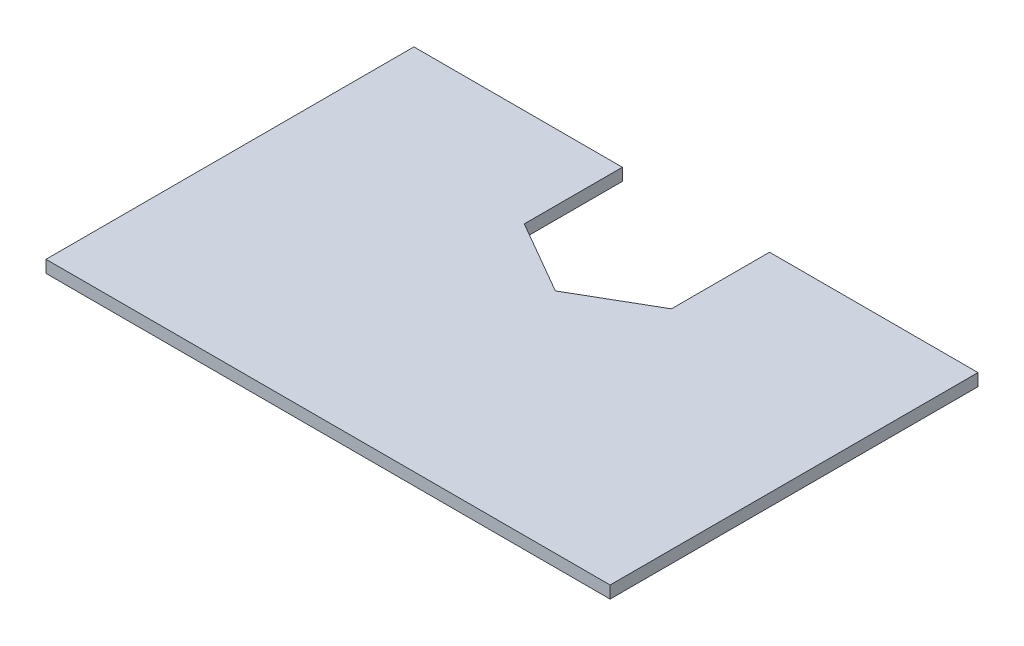
SolidWorks part; units mm, degrees
material "PMMA"
ref_plane "前视基准面" through (0, 0, 0) normal (0, 0, 1) x (1, 0, 0)
ref_plane "上视基准面" through (0, 0, 0) normal (0, 1, 0) x (1, 0, 0)
ref_plane "右视基准面" through (0, 0, 0) normal (1, 0, 0) x (0, 0, -1)
sketch "Sketch1" plane through (0, 0, 0) normal (0, 1, 0) x (1, 0, 0)
  line L0 (0, 0) -> (230, 0)
  line L1 (230, 0) -> (230, -150)
  line L2 (230, -150) -> (0, -150)
  line L3 (0, -150) -> (0, 0)
  dimension "D1" = 230
  dimension "D2" = 150
extrude "Boss-Extrude1" add sketch "Sketch1" along normal blind 5
sketch "Sketch2" plane through (0, 5, 0) normal (0, 1, 0) x (1, 0, 0)
  line L0 (115, 4.0955) -> (115, -154.5763) construction
  line L2 (145, 0) -> (85, 0)
  line L3 (230, 0) -> (0, 0) construction
  line L4 (85, 0) -> (85, -40)
  line L5 (85, -40) -> (115, -57.3205)
  line L6 (145, -40) -> (115, -57.3205)
  line L7 (145, 0) -> (145, -40)
  point P12 (115, 0)
  dimension "D2" = 40
  dimension "D3" = 60
  dimension "D4" = 30
extrude "Cut-Extrude1" cut sketch "Sketch2" against normal through all
